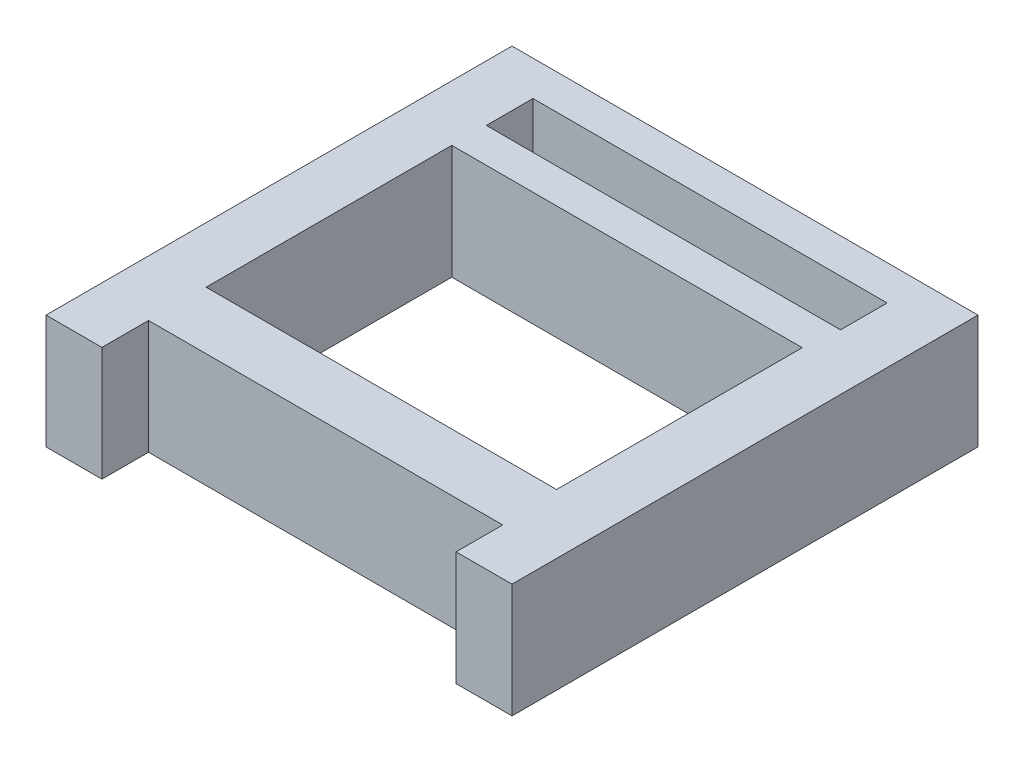
SolidWorks part; units mm, degrees
ref_plane "Front Plane" through (0, 0, 0) normal (0, 0, 1) x (1, 0, 0)
ref_plane "Top Plane" through (0, 0, 0) normal (0, 1, 0) x (1, 0, 0)
ref_plane "Right Plane" through (0, 0, 0) normal (1, 0, 0) x (0, 0, -1)
sketch "Sketch1" plane through (0, 0, 0) normal (0, 1, 0) x (1, 0, 0)
  line L0 (2.4, 0) -> (2.4, 2.473) construction
  line L9 (2.4, 0) -> (17.6, 0)
  line L10 (0, 0) -> (0, 18)
  line L11 (0, 18) -> (20, 18)
  line L12 (20, 0) -> (20, 18)
  line L14 (0, 0) -> (0, -2)
  line L15 (0, -2) -> (2.4, -2)
  line L16 (2.4, 0) -> (2.4, -2)
  line L18 (20, 0) -> (20, -2)
  line L19 (20, -2) -> (17.6, -2)
  line L20 (17.6, 0) -> (17.6, -2)
  line L21 (2.4, 18) -> (2.4, 13.0161) construction
  line L23 (2.4, 13.0161) -> (17.4392, 13.0161)
  line L24 (2.4, 13.0161) -> (2.4, 2.473)
  line L25 (2.4, 2.473) -> (17.4392, 2.473)
  line L26 (17.4392, 13.0161) -> (17.4392, 2.473)
  line L27 (2.4, 16.5) -> (17.6, 16.5)
  line L28 (2.4, 16.5) -> (2.4, 14.5)
  line L29 (2.4, 14.5) -> (17.6, 14.5)
  line L30 (17.6, 16.5) -> (17.6, 14.5)
  dimension "D1" = 18
  dimension "D2" = 20
  dimension "D3" = 2
  dimension "D4" = 2.4
  dimension "D5" = 2
  dimension "D6" = 2.4
  dimension "D7" = 2
  dimension "D8" = 1.5
extrude "Boss-Extrude1" add sketch "Sketch1" along normal blind 4.9
